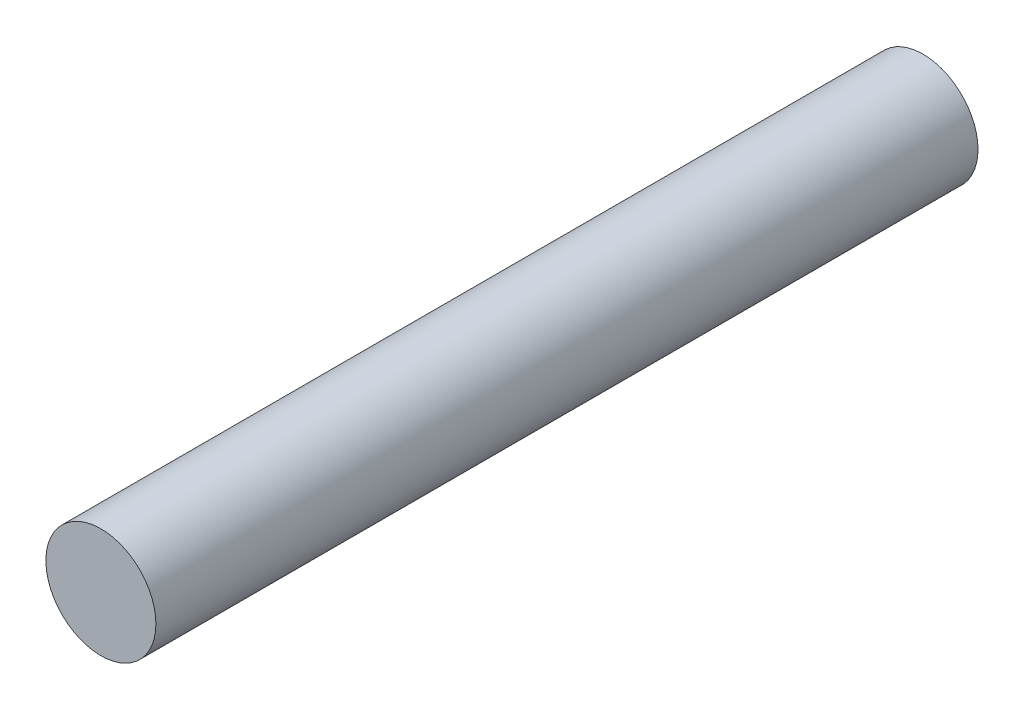
SolidWorks part; units mm, degrees
ref_plane "前视基准面" through (0, 0, 0) normal (0, 0, 1) x (1, 0, 0)
ref_plane "上视基准面" through (0, 0, 0) normal (0, 1, 0) x (1, 0, 0)
ref_plane "右视基准面" through (0, 0, 0) normal (1, 0, 0) x (0, 0, -1)
sketch "草图1" plane through (0, 0, 0) normal (0, 0, 1) x (1, 0, 0)
  circle A0 centre (0, 0) radius 0.95
  dimension "D1" = 1.9
extrude "凸台-拉伸1" add sketch "草图1" along normal blind 14.2 contours A0
